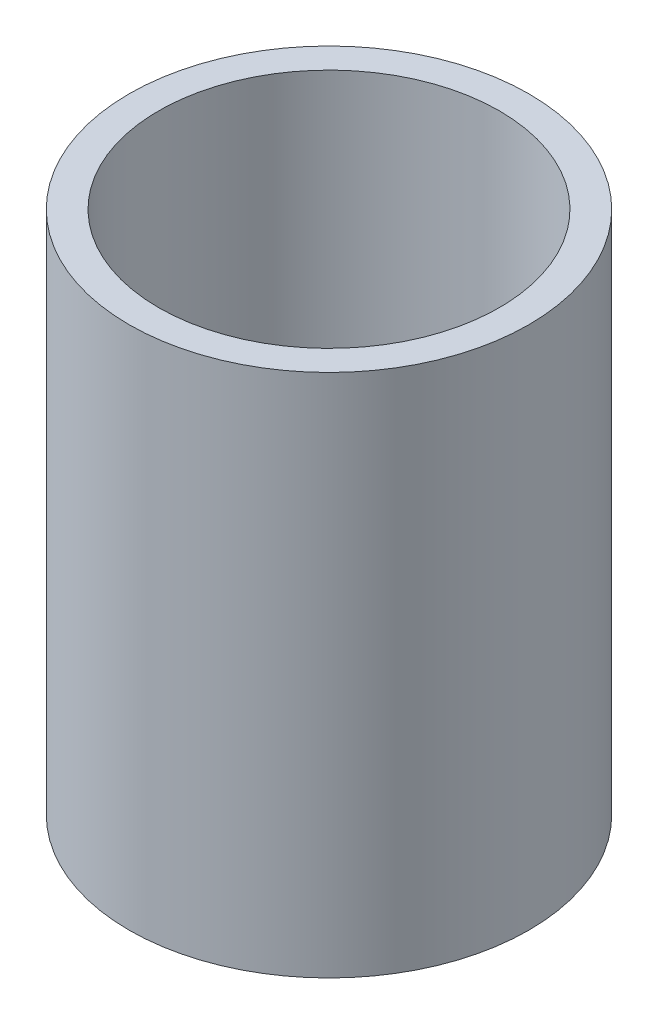
SolidWorks part; units mm, degrees
material "ABS PC"
ref_plane "Front Plane" through (0, 0, 0) normal (0, 0, 1) x (1, 0, 0)
ref_plane "Top Plane" through (0, 0, 0) normal (0, 1, 0) x (1, 0, 0)
ref_plane "Right Plane" through (0, 0, 0) normal (1, 0, 0) x (0, 0, -1)
sketch "Sketch1" plane through (0, 0, 0) normal (0, 1, 0) x (1, 0, 0)
  circle A0 centre (0, 0) radius 15.25
  circle A1 centre (0, 0) radius 13
  dimension "D1" = 26
  dimension "D2" = 30.5
extrude "Boss-Extrude1" add sketch "Sketch1" along normal blind 40
